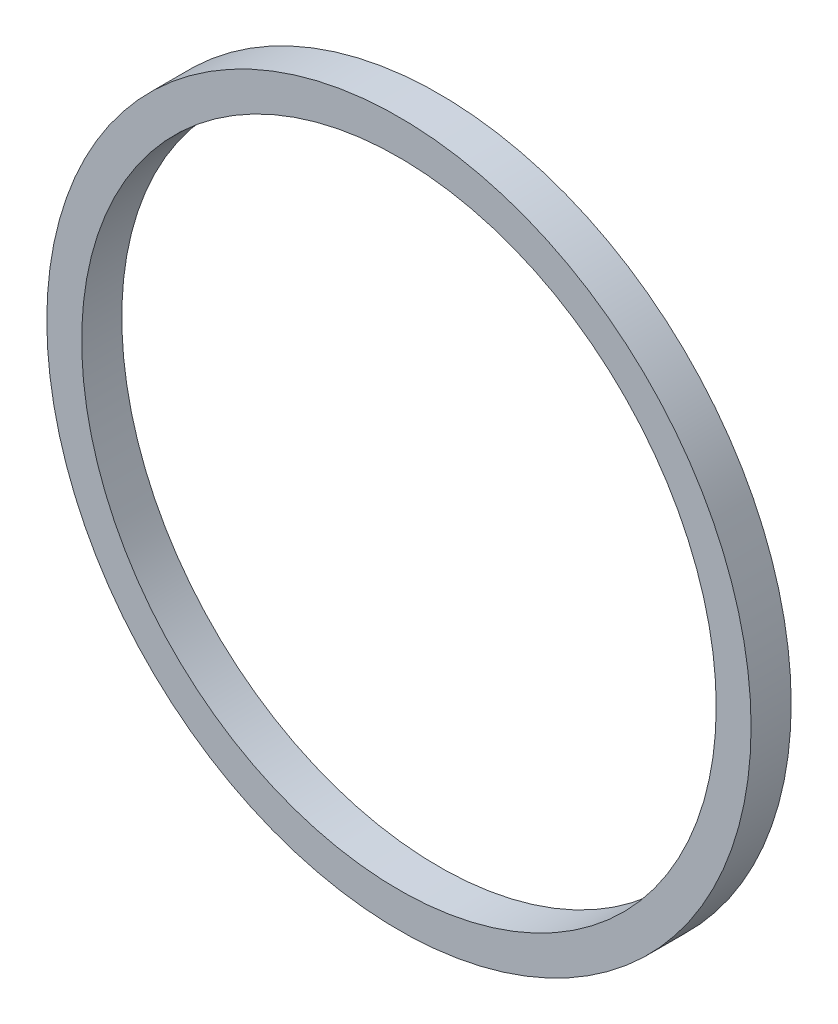
SolidWorks part; units mm, degrees
ref_plane "Front Plane" through (0, 0, 0) normal (0, 0, 1) x (1, 0, 0)
ref_plane "Top Plane" through (0, 0, 0) normal (0, 1, 0) x (1, 0, 0)
ref_plane "Right Plane" through (0, 0, 0) normal (1, 0, 0) x (0, 0, -1)
sketch "Sketch1" plane through (0, 0, 0) normal (0, 0, 1) x (1, 0, 0)
  circle A0 centre (0, 0) radius 10.1
  dimension "D1" = 20.2
extrude "Boss-Extrude1" add sketch "Sketch1" along normal blind 1.15
sketch "Sketch2" plane through (0, 0, 1.15) normal (0, 0, 1) x (1, 0, 0)
  circle A0 centre (0, 0) radius 9.1
  circle A1 centre (0, 0) radius 10.1 construction
  dimension "D1" = 1
extrude "Cut-Extrude1" cut sketch "Sketch2" against normal blind 1.15
